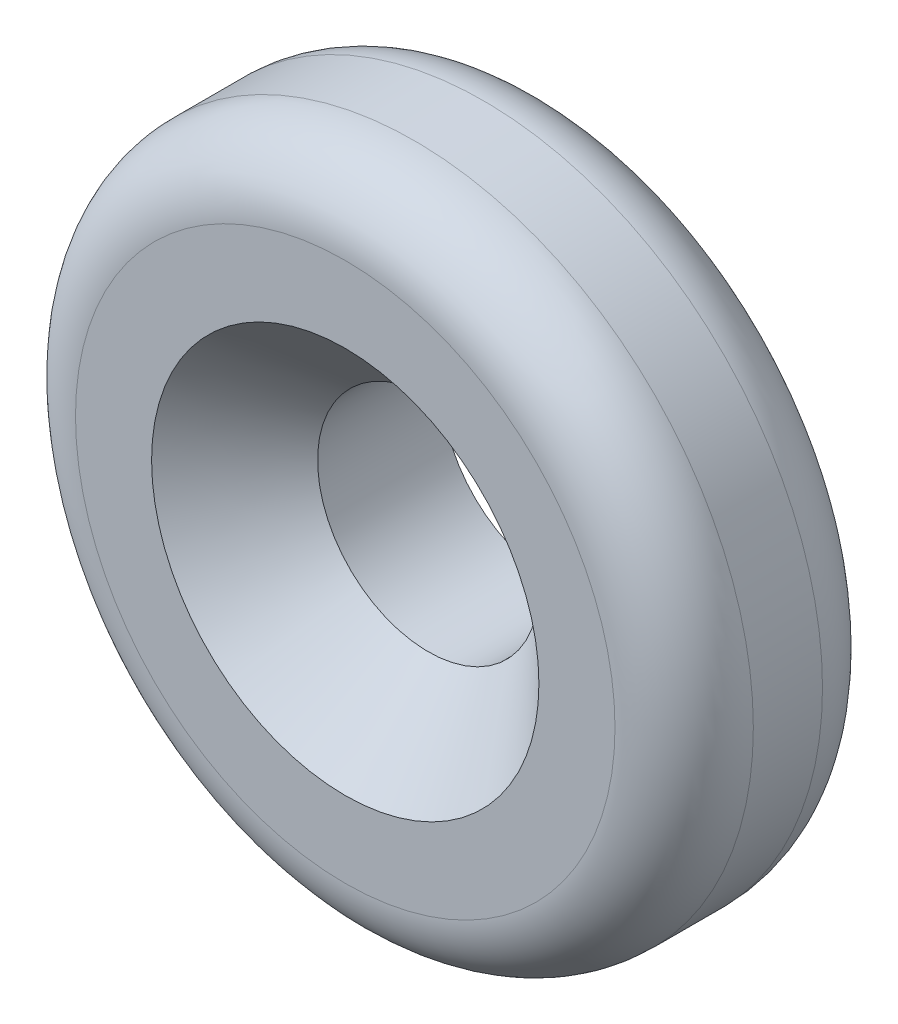
SolidWorks part; units mm, degrees
ref_plane "前视基准面" through (0, 0, 0) normal (0, 0, 1) x (1, 0, 0)
ref_plane "上视基准面" through (0, 0, 0) normal (0, 1, 0) x (1, 0, 0)
ref_plane "右视基准面" through (0, 0, 0) normal (1, 0, 0) x (0, 0, -1)
other "Configuration Table"
sketch "草图1" plane through (0, 0, 0) normal (0, 0, 1) x (1, 0, 0)
  circle A0 centre (0, 0) radius 4.9
  dimension "D1" = 9.8
extrude "凸台-拉伸1" add sketch "草图1" along normal blind 3
sketch "草图2" plane through (0, 0, 3) normal (0, 0, 1) x (1, 0, 0)
  circle A0 centre (0, 0) radius 1.6
  dimension "D1" = 3.2
extrude "切除-拉伸1" cut sketch "草图2" against normal through all
chamfer "倒角1" distance 1.2 angle 45 1 edges at (1.6, 0, 3)
fillet "圆角1" radius 1 1 edges at (4.9, 0, 3)
fillet "圆角2" radius 1 1 edges at (4.9, 0, 0)
